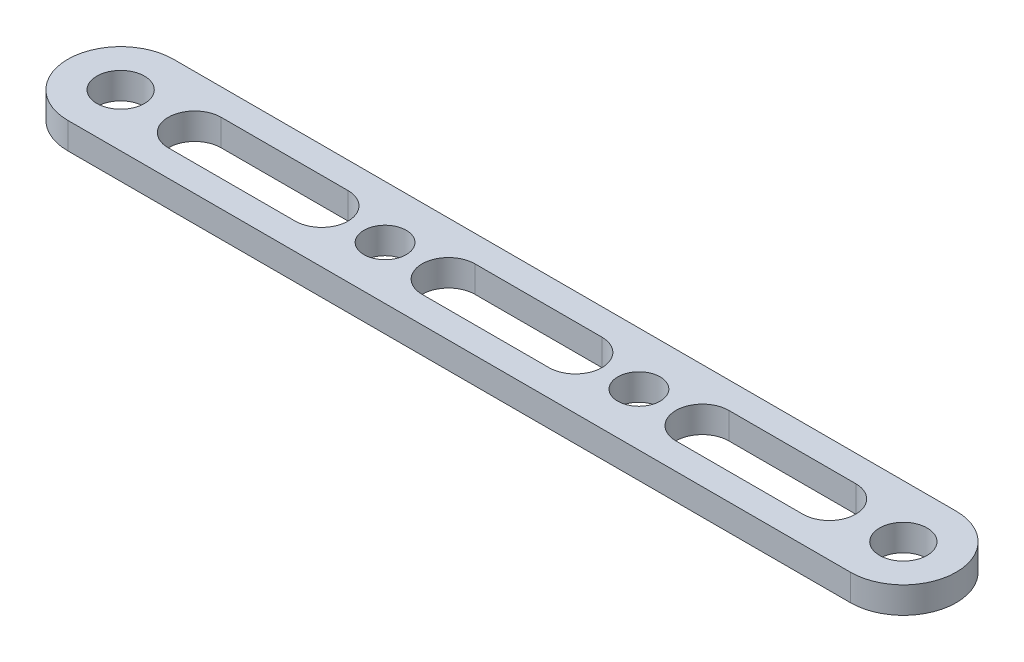
SolidWorks part; units mm, degrees
material "Thornel Mat VMA"
ref_plane "前视基准面" through (0, 0, 0) normal (0, 0, 1) x (1, 0, 0)
ref_plane "上视基准面" through (0, 0, 0) normal (0, 1, 0) x (1, 0, 0)
ref_plane "右视基准面" through (0, 0, 0) normal (1, 0, 0) x (0, 0, -1)
other "Configuration Table"
sketch "草图1" plane through (0, 0, 0) normal (0, 1, 0) x (1, 0, 0)
  line L0 (-74, 0) -> (74, 0) construction
  line L1 (-74, 10) -> (74, 10)
  line L2 (-74, -10) -> (74, -10)
  line L3 (-60, 0) -> (-36, 0) construction
  line L4 (-60, 5) -> (-36, 5)
  line L5 (-60, -5) -> (-36, -5)
  line L6 (-12, 0) -> (12, 0) construction
  line L7 (-12, 5) -> (12, 5)
  line L8 (-12, -5) -> (12, -5)
  line L9 (0, -30.2728) -> (0, 23.7085) construction
  line L10 (60, 0) -> (36, 0) construction
  line L11 (60, 5) -> (36, 5)
  line L12 (60, -5) -> (36, -5)
  arc A0 (-74, 10) -> (-74, -10) centre (-74, 0) ccw
  arc A1 (74, -10) -> (74, 10) centre (74, 0) ccw
  circle A2 centre (74, 0) radius 4.5
  circle A3 centre (-74, 0) radius 4.5
  arc A4 (-60, 5) -> (-60, -5) centre (-60, 0) ccw
  arc A5 (-36, -5) -> (-36, 5) centre (-36, 0) ccw
  arc A6 (-12, 5) -> (-12, -5) centre (-12, 0) ccw
  arc A7 (12, -5) -> (12, 5) centre (12, 0) ccw
  circle A8 centre (-24, 0) radius 4
  arc A9 (60, 5) -> (60, -5) centre (60, 0) cw
  arc A10 (36, -5) -> (36, 5) centre (36, 0) cw
  circle A11 centre (24, 0) radius 4
  point P3 (0, 0)
  point P14 (-48, 0)
  point P19 (0, 0)
  point P32 (48, 0)
  dimension "D2" = 9
  dimension "D3" = 10
  dimension "D6" = 8
  dimension "D8" = 5
  dimension "D1" = 148
  dimension "D4" = 24
  dimension "D5" = 24
  dimension "D7" = 14
  dimension "D9" = 12
extrude "凸台-拉伸1" add sketch "草图1" along normal blind 5
